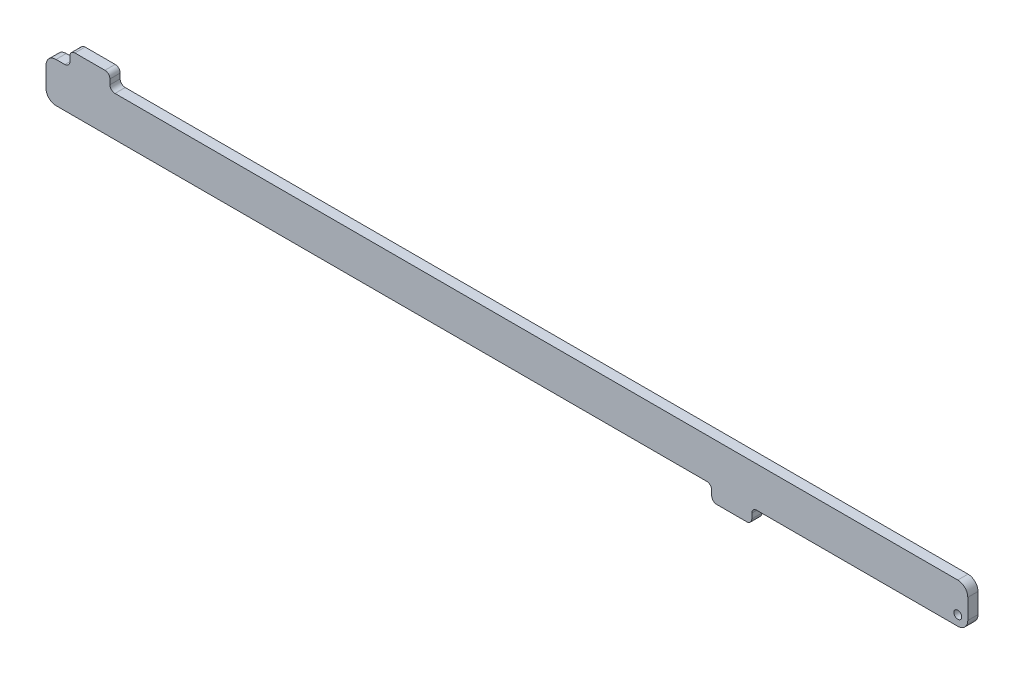
SolidWorks part; units mm, degrees
material "PC High Viscosity"
ref_plane "Front Plane" through (0, 0, 0) normal (0, 0, 1) x (1, 0, 0)
ref_plane "Top Plane" through (0, 0, 0) normal (0, 1, 0) x (1, 0, 0)
ref_plane "Right Plane" through (0, 0, 0) normal (1, 0, 0) x (0, 0, -1)
sketch "Sketch1" plane through (0, 0, 0) normal (0, 0, 1) x (1, 0, 0)
  line L1 (0, 0) -> (40.5308, 0)
  line L2 (0, 0) -> (0, 25.4)
  line L3 (0, 25.4) -> (15.1307, 25.4)
  line L4 (584.2, 0) -> (584.2, 25.4)
  line L5 (15.1307, 34.925) -> (40.5307, 34.925)
  line L6 (40.5307, 34.925) -> (40.5307, 25.4)
  line L7 (15.1307, 34.925) -> (15.1307, 25.4)
  line L11 (584.2, 10.0162) -> (577.85, 13.6823) construction
  line L12 (577.85, 13.6823) -> (571.5, 10.0162) construction
  line L13 (571.5, 10.0162) -> (571.5, 2.6838) construction
  line L14 (571.5, 2.6838) -> (577.85, -0.9823) construction
  line L15 (577.85, -0.9823) -> (584.2, 2.6838) construction
  line L16 (584.2, 2.6838) -> (584.2, 10.0162) construction
  line L19 (421.9033, 0) -> (421.9033, -9.525)
  line L20 (421.9033, -9.525) -> (447.3033, -9.525)
  line L21 (447.3033, -9.525) -> (447.3033, 0)
  line L22 (40.5307, 25.4) -> (584.2, 25.4)
  line L23 (40.5308, 0) -> (421.9033, 0)
  line L24 (447.3033, 0) -> (584.2, 0)
  circle A0 centre (577.85, 6.35) radius 2.4892
  circle A1 centre (577.85, 6.35) radius 6.35 construction
  dimension "D5" = 4.9784
  dimension "D6" = 9.525
  dimension "D7" = 12.7
  dimension "D1" = 584.2
  dimension "D2" = 25.4
  dimension "D3" = 25.4
  dimension "D4" = 421.9033
  dimension "D8" = 40.5307
  dimension "D9" = 25.4
extrude "Boss-Extrude1" add sketch "Sketch1" along normal blind 6.477
fillet "Fillet2" radius 6.35 4 edges at (0, 0, 3.2385) (0, 25.4, 3.2385) (584.2, 25.4, 3.2385) (584.2, 0, 3.2385)
sketch "Sketch2" plane through (0, 0, 6.477) normal (0, 0, 1) x (1, 0, 0)
  line L0 (6.35, 25.4) -> (15.1307, 25.4) construction
  line L1 (584.2, 19.05) -> (584.2, 6.35) construction
  circle A0 centre (546.1, 12.7) radius 2.0193
  dimension "D1" = 4.0386
  dimension "D2" = 12.7
  dimension "D3" = 38.1
mirror "Mirror2" about plane through (0, 0, 0) normal (0, 0, 1) of bodies 101 108
delete or keep bodies "Body-Delete/Keep 1" type delete bodies bodies 101
fillet "Fillet3" radius 3.175 8 edges at (447.3033, 0, -3.2385) (447.3033, -9.525, -3.2385) (421.9033, -9.525, -3.2385) (421.9033, 0, -3.2385) (40.5307, 25.4, -3.2385) (40.5307, 34.925, -3.2385) (15.1307, 34.925, -3.2385) (15.1307, 25.4, -3.2385)
